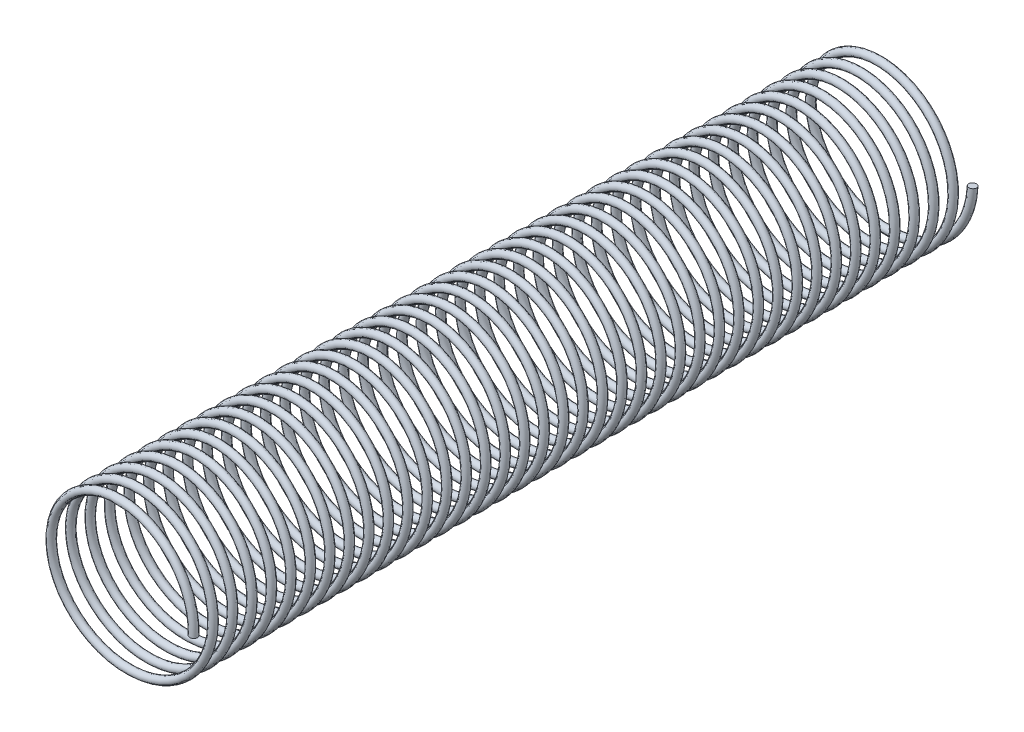
SolidWorks part; units mm, degrees
ref_plane "Front Plane" through (0, 0, 0) normal (0, 0, 1) x (1, 0, 0)
ref_plane "Top Plane" through (0, 0, 0) normal (0, 1, 0) x (1, 0, 0)
ref_plane "Right Plane" through (0, 0, 0) normal (1, 0, 0) x (0, 0, -1)
sketch "Esquisse1" plane through (0, 0, 0) normal (0, 0, 1) x (1, 0, 0)
  circle A0 centre (1.5, 0) radius 2
  dimension "D1" = 4
  dimension "D2" = 1.5
curve "Hélice/Spirale1" pitch 0.5125 height 20.5 turns 40
sweep "Balayage3" add path "Hélice/Spirale1" circular profile diameter 0.2 parameters "D3"=0.2
sketch "Esquisse50" plane through (0, 0, 0) normal (0, 1, 0) x (1, 0, 0)
  line L0 (1.5692, -21.6266) -> (1.5692, 3.4389) construction
